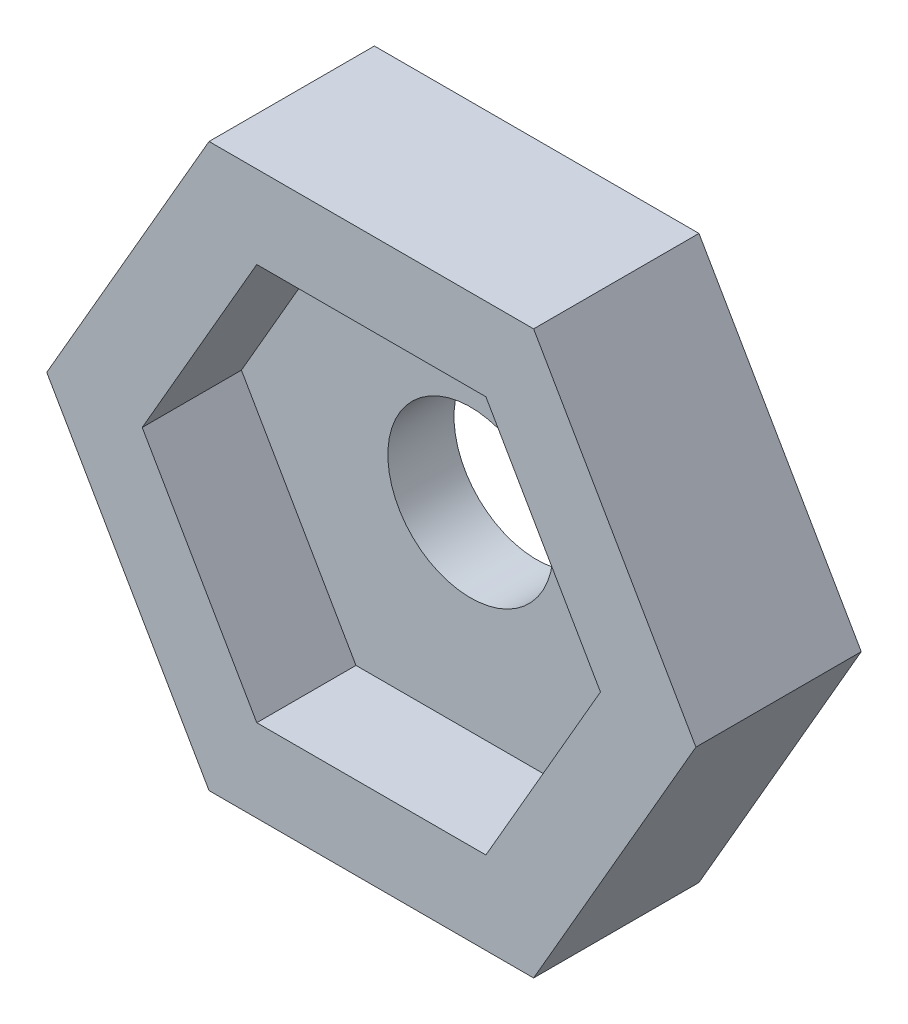
SolidWorks part; units mm, degrees
ref_plane "Front Plane" through (0, 0, 0) normal (0, 0, 1) x (1, 0, 0)
ref_plane "Top Plane" through (0, 0, 0) normal (0, 1, 0) x (1, 0, 0)
ref_plane "Right Plane" through (0, 0, 0) normal (1, 0, 0) x (0, 0, -1)
sketch "Sketch1" plane through (0, 0, 0) normal (0, 0, 1) x (1, 0, 0)
  line L0 (0, 8.5) -> (0, 0) construction
  line L1 (4.9075, -8.5) -> (9.815, 0)
  line L2 (9.815, 0) -> (4.9075, 8.5)
  line L3 (4.9075, 8.5) -> (-4.9075, 8.5)
  line L4 (-4.9075, 8.5) -> (-9.815, 0)
  line L5 (-9.815, 0) -> (-4.9075, -8.5)
  line L6 (-4.9075, -8.5) -> (4.9075, -8.5)
  circle A0 centre (0, 0) radius 8.5 construction
  circle A1 centre (0, 0) radius 2.5
  dimension "D2" = 5
  dimension "D1" = 17
extrude "Boss-Extrude1" add sketch "Sketch1" along normal blind 5 contours L5 L6 L1 L2 L3 L4 A1
sketch "Sketch2" plane through (0, 0, 5) normal (0, 0, 1) x (1, 0, 0)
  line L0 (0, 6) -> (0, 0) construction
  line L1 (3.4641, -6) -> (6.9282, 0)
  line L2 (6.9282, 0) -> (3.4641, 6)
  line L3 (3.4641, 6) -> (-3.4641, 6)
  line L4 (-3.4641, 6) -> (-6.9282, 0)
  line L5 (-6.9282, 0) -> (-3.4641, -6)
  line L6 (-3.4641, -6) -> (3.4641, -6)
  circle A0 centre (0, 0) radius 6 construction
  dimension "D1" = 12
extrude "Cut-Extrude1" cut sketch "Sketch2" against normal blind 3
